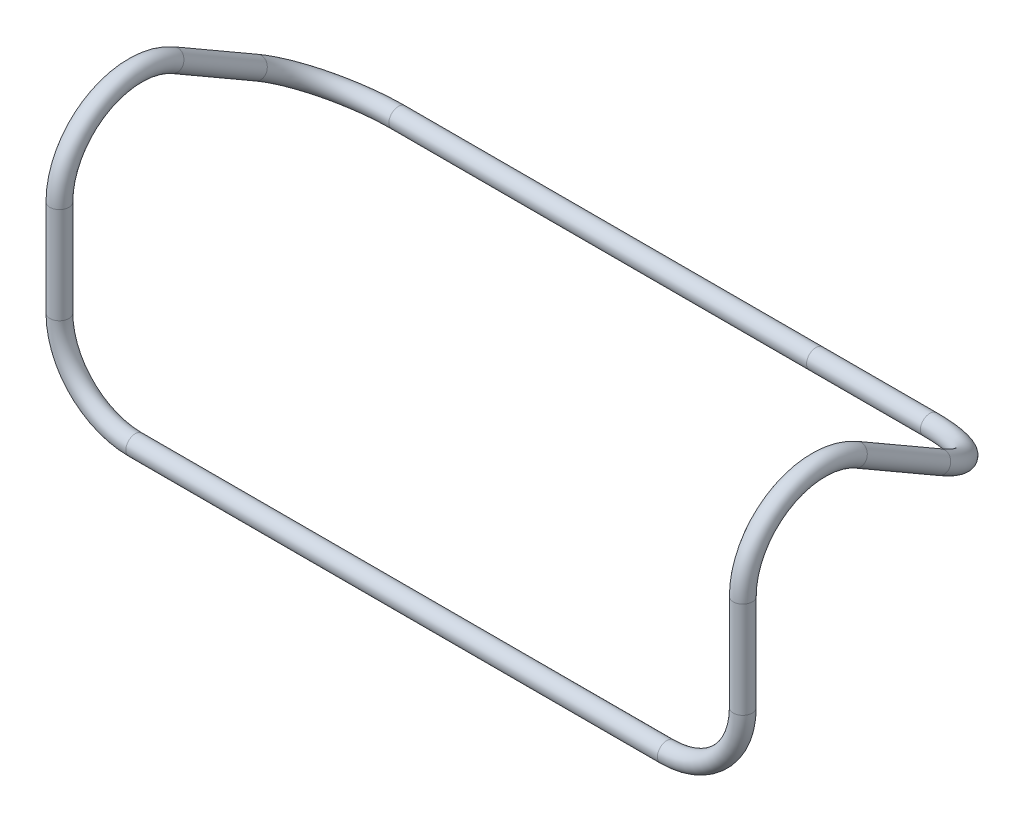
SolidWorks part; units mm, degrees
ref_plane "前视基准面" through (0, 0, 0) normal (0, 0, 1) x (1, 0, 0)
ref_plane "上视基准面" through (0, 0, 0) normal (0, 1, 0) x (1, 0, 0)
ref_plane "右视基准面" through (0, 0, 0) normal (1, 0, 0) x (0, 0, -1)
other "Configuration Table"
sketch3d "3D草图3"
  line L0 (0, 20, 0) -> (0, 45.359, 0)
  line L1 (0, 62.6795, -30) -> (0, 50, -51.9615)
  line L2 (-20, 40, -69.282) -> (-160, 40, -69.282)
  line L3 (-180, 50, -51.9615) -> (-180, 62.6795, -30)
  line L4 (-180, 45.359, 0) -> (-180, 20, 0)
  line L5 (-160, 0, 0) -> (-20, 0, 0)
  arc A0 (-180, 50, -51.9615) -> (-160, 40, -69.282) centre (-160, 50, -51.9615) ccw
  arc A1 (-180, 62.6795, -30) -> (-180, 45.359, 0) centre (-180, 45.359, -20) ccw
  arc A2 (-180, 20, 0) -> (-160, 0, 0) centre (-160, 20, 0) ccw
  arc A3 (0, 45.359, 0) -> (0, 62.6795, -30) centre (0, 45.359, -20) ccw
  arc A4 (-20, 0, 0) -> (0, 20, 0) centre (-20, 20, 0) ccw
  arc A5 (0, 50, -51.9615) -> (-20, 40, -69.282) centre (-20, 50, -51.9615) ccw
  point P20 (-180, 40, -69.282)
  point P21 (-160, 32.6795, -41.9615)
  point P24 (-180, 80, 0)
  point P25 (-160, 45.359, -20)
  point P28 (-180, 0, 0)
  point P29 (-160, 20, 20)
  point P32 (0, 80, 0)
  point P33 (-20, 45.359, -20)
  point P36 (0, 0, 0)
  point P37 (-20, 20, 20)
  point P40 (0, 40, -69.282)
  point P41 (-20, 67.3205, -61.9615)
  dimension "D8" = 20
  dimension "D1" = 60
  dimension "D2" = 80
  dimension "D3" = 80
  dimension "D4" = 180
  dimension "D5" = 180
  dimension "D6" = 90
  dimension "D7" = 80
ref_plane "基准面1" through (-50, 0, 0) normal (1, 0, 0) x (0, 0, -1)
sketch "草图3" plane through (-50, 0, 0) normal (1, 0, 0) x (0, 0, -1)
  circle A0 centre (69.282, 40) radius 2.5
  dimension "D1" = 5
sweep "扫描1" add profiles "草图3" path "3D草图3"
